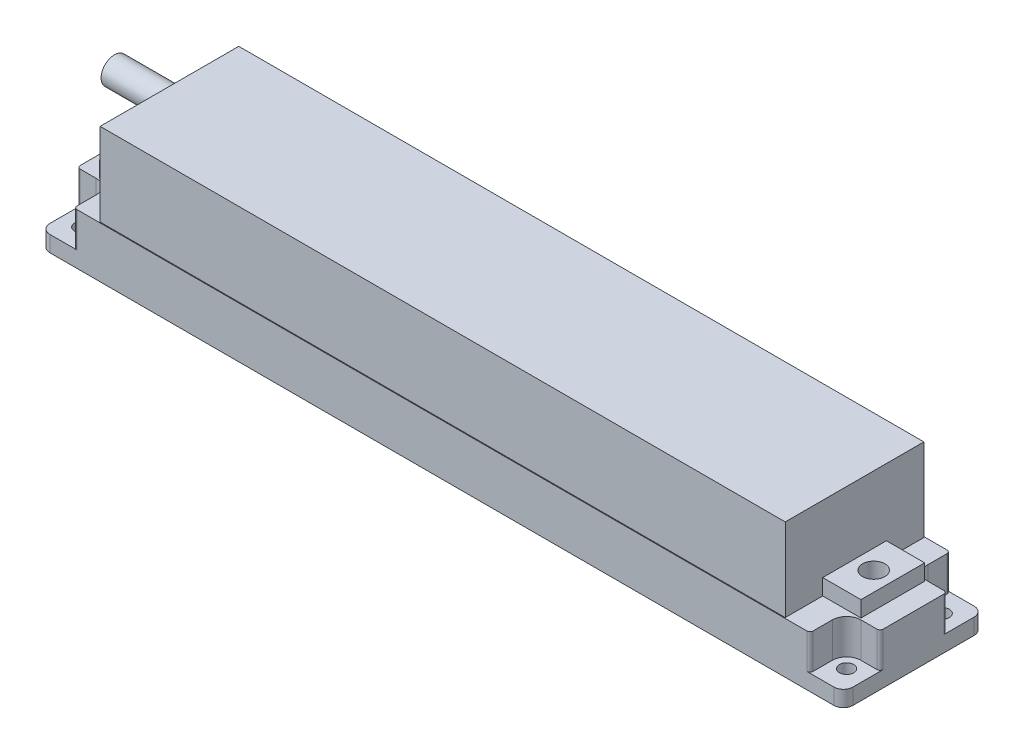
SolidWorks part; units mm, degrees
ref_plane "正面" through (0, 0, 0) normal (0, 0, 1) x (1, 0, 0)
ref_plane "平面" through (0, 0, 0) normal (0, 1, 0) x (1, 0, 0)
ref_plane "右側面" through (0, 0, 0) normal (1, 0, 0) x (0, 0, -1)
sketch "ｽｹｯﾁ1" plane through (0, 0, 0) normal (0, 1, 0) x (1, 0, 0)
  line L1 (-107.5, 21.75) -> (107.5, 21.75)
  line L2 (-107.5, 21.75) -> (-107.5, -21.75)
  line L3 (-107.5, -21.75) -> (107.5, -21.75)
  line L4 (107.5, 21.75) -> (107.5, -21.75)
  point P4 (0, 21.75)
  point P6 (-107.5, 0)
  dimension "D1" = 43.5
  dimension "D2" = 215
extrude "ﾎﾞｽ - 押し出し1" add sketch "ｽｹｯﾁ1" along normal blind 26
sketch "ｽｹｯﾁ2" plane through (0, 0, 0) normal (0, -1, 0) x (1, 0, 0)
  line L0 (0, -21.75) -> (0, 21.75) construction
  line L1 (-119.5, -10) -> (-107.5, -10)
  line L2 (-119.5, -10) -> (-119.5, 10)
  line L3 (-119.5, 10) -> (-107.5, 10)
  line L4 (-107.5, -10) -> (-107.5, 10)
  line L5 (107.5, -21.75) -> (-107.5, -21.75) construction
  line L6 (-107.5, 21.75) -> (107.5, 21.75) construction
  line L7 (-107.5, -21.75) -> (-107.5, 21.75) construction
  line L8 (107.5, -10) -> (107.5, 10)
  line L9 (119.5, 10) -> (107.5, 10)
  line L10 (119.5, -10) -> (119.5, 10)
  line L11 (119.5, -10) -> (107.5, -10)
  circle A0 centre (-113.5, 0) radius 3.5
  circle A1 centre (113.5, 0) radius 3.5
  point P12 (-119.5, 0)
  point P17 (-113.5, 10)
  dimension "D3" = 7
  dimension "D1" = 12
  dimension "D2" = 20
extrude "ﾎﾞｽ - 押し出し2" add sketch "ｽｹｯﾁ2" against normal blind 5
sketch "ｽｹｯﾁ3" plane through (-107.5, 0, 0) normal (-1, 0, 0) x (0, 0, 1)
  line L0 (-21.75, 26) -> (-21.75, 0) construction
  line L1 (-21.75, 26) -> (21.75, 26) construction
  circle A0 centre (-7.75, 14) radius 4.2
  dimension "D1" = 14
  dimension "D3" = 8.4
  dimension "D2" = 12
extrude "ﾎﾞｽ - 押し出し3" add sketch "ｽｹｯﾁ3" along normal blind 25
sketch "ｽｹｯﾁ4" plane through (0, 0, 0) normal (0, -1, 0) x (1, 0, 0)
  line L0 (-113.5, 0) -> (113.5, 0) construction
  line L1 (-120, -15) -> (120, -15) construction
  line L2 (-120, -15) -> (-120, 15) construction
  line L3 (-120, 15) -> (120, 15) construction
  line L4 (120, -15) -> (120, 15) construction
  line L6 (-126, -22) -> (126, -22)
  line L7 (-126, -22) -> (-126, 22)
  line L8 (-126, 22) -> (126, 22)
  line L9 (126, -22) -> (126, 22)
  line L10 (-100, -17) -> (100, -17)
  line L11 (-100, -17) -> (-100, 17)
  line L12 (-100, 17) -> (100, 17)
  line L13 (100, -17) -> (100, 17)
  circle A0 centre (-120, -15) radius 2.25
  circle A1 centre (-120, 15) radius 2.25
  circle A2 centre (120, 15) radius 2.25
  circle A3 centre (120, -15) radius 2.25
  circle A4 centre (-113.5, 0) radius 2.6
  circle A5 centre (113.5, 0) radius 2.6
  point P8 (120, 0)
  point P9 (0, -15)
  point P14 (-126, 0)
  point P16 (0, -22)
  point P28 (0, 17)
  dimension "D3" = 4.5
  dimension "D6" = 5.2
  dimension "D1" = 240
  dimension "D2" = 30
  dimension "D4" = 7
  dimension "D5" = 6
  dimension "D7" = 44
  dimension "D8" = 5
  dimension "D9" = 200
extrude "ﾎﾞｽ - 押し出し4" add sketch "ｽｹｯﾁ4" along normal blind 16 separate body
sketch "ｽｹｯﾁ5" plane through (0, 0, 0) normal (0, 1, 0) x (1, 0, 0)
  line L0 (126, -22) -> (-126, -22) construction
  line L1 (-126, -22) -> (-115.5, -22)
  line L2 (-126, -22) -> (-126, -10.5)
  line L3 (-126, -10.5) -> (-115.5, -10.5)
  line L4 (-115.5, -22) -> (-115.5, -10.5)
  line L5 (-126, -22) -> (-126, 22) construction
  line L6 (0, 22) -> (0, 0) construction
  line L7 (-126, 22) -> (126, 22) construction
  line L8 (0, 0) -> (-126, 0) construction
  line L9 (-115.5, 22) -> (-115.5, 10.5)
  line L10 (-126, 10.5) -> (-115.5, 10.5)
  line L11 (-126, 22) -> (-126, 10.5)
  line L12 (-126, 22) -> (-115.5, 22)
  line L13 (126, 22) -> (115.5, 22)
  line L14 (126, 22) -> (126, 10.5)
  line L15 (126, 10.5) -> (115.5, 10.5)
  line L16 (115.5, 22) -> (115.5, 10.5)
  line L17 (115.5, -22) -> (115.5, -10.5)
  line L18 (126, -10.5) -> (115.5, -10.5)
  line L19 (126, -22) -> (126, -10.5)
  line L20 (126, -22) -> (115.5, -22)
  circle A0 centre (-120, -15) radius 4.5
  circle A1 centre (-120, 15) radius 4.5
  circle A2 centre (120, 15) radius 4.5
  circle A3 centre (120, -15) radius 4.5
  dimension "D1" = 9
extrude "ｶｯﾄ - 押し出し1" cut sketch "ｽｹｯﾁ5" against normal offset from surface (11 mm away) 5
fillet "ﾌｨﾚｯﾄ1" radius 3 4 edges at (-126, -13.5, -22) (-126, -13.5, 22) (126, -13.5, -22) (126, -13.5, 22)
fillet "ﾌｨﾚｯﾄ2" radius 10 4 edges at (100, -8, 17) (100, -8, -17) (-100, -8, 17) (-100, -8, -17)
fillet "ﾌｨﾚｯﾄ3" radius 1 8 edges at (126, -5.5, -10.5) (115.5, -5.5, -22) (115.5, -5.5, 22) (126, -5.5, 10.5) (-126, -5.5, -10.5) (-115.5, -5.5, -22) (-126, -5.5, 10.5) (-115.5, -5.5, 22)
